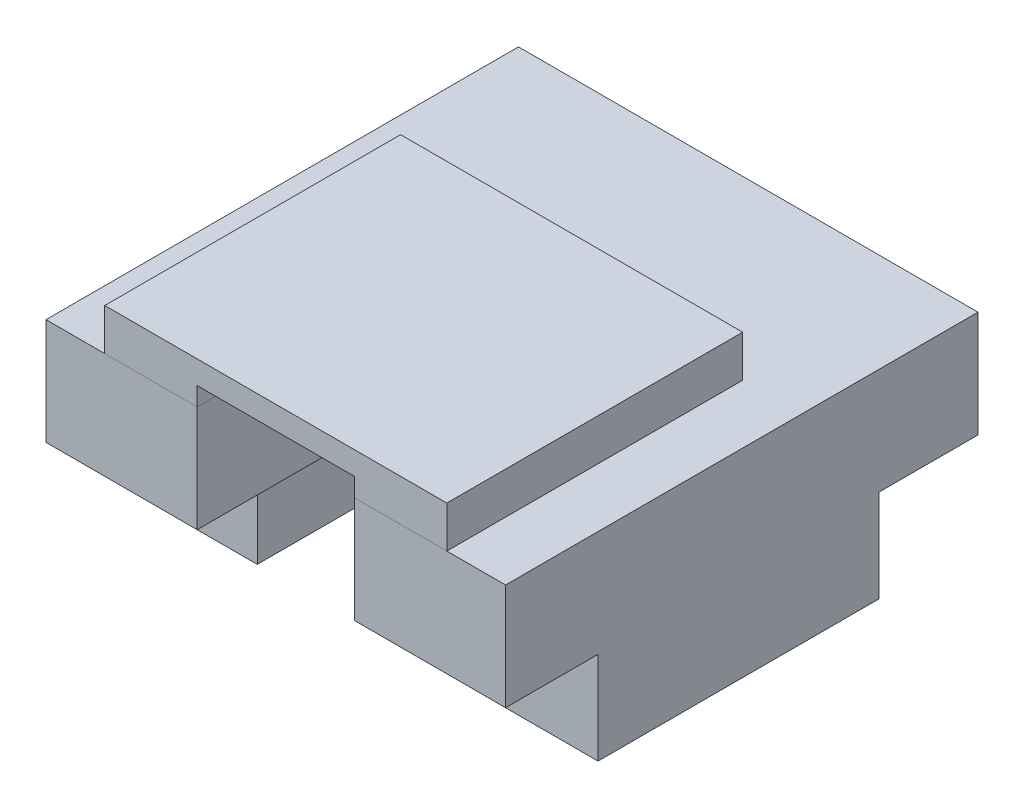
SolidWorks part; units mm, degrees
ref_plane "Front Plane" through (0, 0, 0) normal (0, 0, 1) x (1, 0, 0)
ref_plane "Top Plane" through (0, 0, 0) normal (0, 1, 0) x (1, 0, 0)
ref_plane "Right Plane" through (0, 0, 0) normal (1, 0, 0) x (0, 0, -1)
sketch "Sketch1" plane through (0, 0, 0) normal (0, 1, 0) x (1, 0, 0)
  line L1 (12.425, -7.6) -> (-12.425, -7.6)
  line L2 (12.425, -7.6) -> (12.425, 7.6)
  line L3 (12.425, 7.6) -> (-12.425, 7.6)
  line L4 (-12.425, -7.6) -> (-12.425, 7.6)
  line L5 (12.425, -7.6) -> (-12.425, 7.6) construction
  line L6 (12.425, 7.6) -> (-12.425, -7.6) construction
  point P0 (0, 0)
  dimension "D1" = 15.2
  dimension "D2" = 24.85
extrude "Boss-Extrude1" add sketch "Sketch1" along normal blind 5.75
sketch "Sketch2" plane through (0, 0, 0) normal (0, -1, 0) x (1, 0, 0)
  line L0 (12.425, -7.6) -> (-12.425, -7.6) construction
  line L1 (-12.425, 7.6) -> (-6, 7.6)
  line L2 (-12.425, 7.6) -> (-12.425, -7.6)
  line L3 (-12.425, -7.6) -> (-6, -7.6)
  line L4 (-6, 7.6) -> (-6, -7.6)
  line L5 (-12.425, -7.6) -> (-12.425, 7.6) construction
  line L6 (12.425, 7.6) -> (6, 7.6)
  line L7 (12.425, 7.6) -> (12.425, -7.6)
  line L8 (12.425, -7.6) -> (6, -7.6)
  line L9 (6, 7.6) -> (6, -7.6)
  line L10 (12.425, 7.6) -> (12.425, -7.6) construction
  line L11 (-12.425, 7.6) -> (12.425, 7.6) construction
  dimension "D1" = 12
extrude "Boss-Extrude2" add sketch "Sketch2" along normal blind 5
sketch "Sketch3" plane through (0, 0, -7.6) normal (0, 0, -1) x (-1, 0, 0)
  line L0 (12.425, 5.75) -> (12.425, -5) construction
  line L1 (-12.425, 5.75) -> (12.425, 5.75)
  line L2 (-12.425, 5.75) -> (-12.425, 0)
  line L3 (-12.425, 0) -> (12.425, 0)
  line L4 (12.425, 5.75) -> (12.425, 0)
  line L5 (-6, 0) -> (6, 0) construction
extrude "Boss-Extrude3" add sketch "Sketch3" along normal blind 5.35
sketch "Sketch5" plane through (0, 0, 7.6) normal (0, 0, 1) x (1, 0, 0)
  line L0 (12.425, 5.75) -> (12.425, -5) construction
  line L1 (-12.425, 5.75) -> (12.425, 5.75)
  line L2 (-12.425, 5.75) -> (-12.425, 0)
  line L3 (-12.425, 0) -> (12.425, 0)
  line L4 (12.425, 5.75) -> (12.425, 0)
  line L5 (-6, 0) -> (6, 0) construction
extrude "Boss-Extrude4" add sketch "Sketch5" along normal blind 5
sketch "Sketch6" plane through (0, 5.75, 0) normal (0, 1, 0) x (1, 0, 0)
  line L0 (12.425, -12.6) -> (-12.425, -12.6) construction
  line L1 (-4.25, -1.6) -> (4.25, -1.6)
  line L2 (-4.25, -1.6) -> (-4.25, -12.6)
  line L3 (-4.25, -12.6) -> (4.25, -12.6)
  line L4 (4.25, -1.6) -> (4.25, -12.6)
  line L5 (-4.25, -1.6) -> (4.25, -12.6) construction
  line L6 (-4.25, -12.6) -> (4.25, -1.6) construction
  point P0 (0, -7.1)
  dimension "D1" = 8.5
  dimension "D2" = 11
extrude "Cut-Extrude2" cut sketch "Sketch6" against normal up to surface (5.75 mm away) up to face at (0, 0, -0.0583)
sketch "Sketch4" plane through (0, 0, -12.95) normal (0, 0, -1) x (-1, 0, 0)
  line L0 (-12.425, 0) -> (12.425, 0) construction
  line L1 (-6, 1.5) -> (6, 1.5)
  line L2 (-6, 1.5) -> (-6, 0)
  line L3 (-6, 0) -> (6, 0)
  line L4 (6, 1.5) -> (6, 0)
  line L5 (-6, 1.5) -> (6, 0) construction
  line L6 (-6, 0) -> (6, 1.5) construction
  point P0 (0, 0.75)
  line M6 (-12.425, 0) -> (12.425, 0)
  dimension "D1" = 1.5
  dimension "D2" = 12
extrude "Cut-Extrude1" cut sketch "Sketch4" against normal offset from surface (14.05 mm away) 0.5 contours L4 L1 L2 M6 up to face at (0, 2.875, 1.6)
sketch "Sketch7" plane through (0, 5.75, 0) normal (0, 1, 0) x (1, 0, 0)
  line L14 (12.425, -12.6) -> (4.25, -12.6) construction
  line L15 (4.25, -12.6) -> (4.25, -1.6) construction
  line L24 (4.25, -1.6) -> (-4.25, -1.6) construction
  line L25 (-9.25, 3.4) -> (-9.25, -12.6)
  line L26 (9.25, 3.4) -> (-9.25, 3.4)
  line L27 (9.25, -12.6) -> (9.25, 3.4)
  line L28 (-9.25, 3.4) -> (-9.25, -12.6)
  line L29 (9.25, 3.4) -> (-9.25, 3.4)
  line L30 (9.25, -12.6) -> (9.25, 3.4)
  line L31 (-4.25, -12.6) -> (-12.425, -12.6) construction
  line L32 (-4.25, -1.6) -> (-4.25, -12.6) construction
  line L33 (12.425, -12.6) -> (4.25, -12.6)
  line L34 (4.25, -12.6) -> (4.25, -1.6)
  line L35 (4.25, -1.6) -> (-4.25, -1.6)
  line L36 (-4.25, -12.6) -> (-12.425, -12.6)
  line L37 (-4.25, -1.6) -> (-4.25, -12.6)
  line M8 (4.25, -1.6) -> (4.25, -12.6)
  line M9 (4.25, -12.6) -> (12.425, -12.6)
  line M13 (-12.425, -12.6) -> (-4.25, -12.6)
  line M14 (-4.25, -12.6) -> (-4.25, -1.6)
  line M15 (-4.25, -1.6) -> (4.25, -1.6)
  dimension "D2" = 5
extrude "Boss-Extrude5" add sketch "Sketch7" along normal blind 1 separate body contours L30 L29 L28 M9 M13 M14 M15 M8
sketch "Sketch8" plane through (0, 6.75, 0) normal (0, 1, 0) x (1, 0, 0)
  line L1 (-9.25, 3.4) -> (9.25, 3.4)
  line L2 (-9.25, 3.4) -> (-9.25, -12.6)
  line L3 (-9.25, -12.6) -> (9.25, -12.6)
  line L4 (9.25, 3.4) -> (9.25, -12.6)
extrude "Boss-Extrude6" add sketch "Sketch8" along normal blind 1.25
